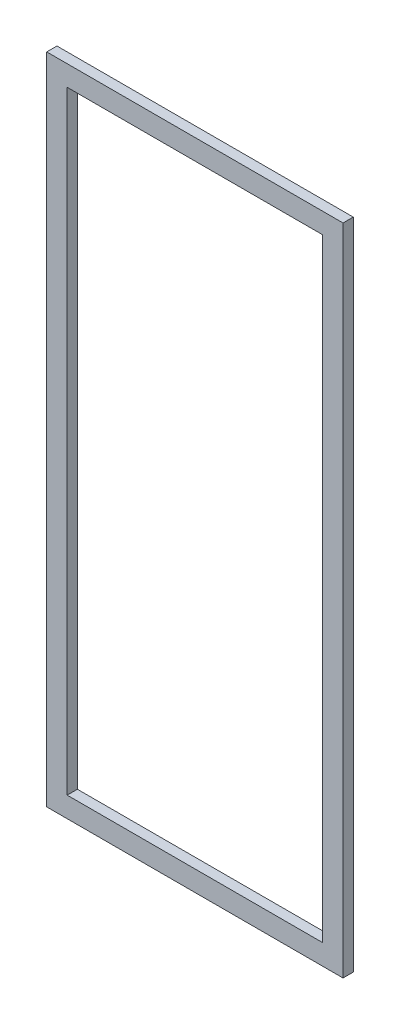
SolidWorks part; units mm, degrees
ref_plane "FP" through (0, 0, 0) normal (0, 0, 1) x (1, 0, 0)
ref_plane "TP" through (0, 0, 0) normal (0, 1, 0) x (1, 0, 0)
ref_plane "RP" through (0, 0, 0) normal (1, 0, 0) x (0, 0, -1)
sketch "Sketch2" plane through (0, 0, 0) normal (0, 0, 1) x (1, 0, 0)
  line L6 (-14.5, -32) -> (14.5, -32)
  line L7 (-14.5, -32) -> (-14.5, 32)
  line L8 (-14.5, 32) -> (14.5, 32)
  line L9 (14.5, -32) -> (14.5, 32)
  dimension "D1" = 64
  dimension "D2" = 32
  dimension "D3" = 29
  dimension "D4" = 14.5
extrude "Boss-Extrude1" add sketch "Sketch2" against normal blind 1
sketch "Sketch3" plane through (0, 0, 0) normal (0, 0, 1) x (1, 0, 0)
  line L1 (-12.5, -30) -> (12.5, -30)
  line L2 (-12.5, -30) -> (-12.5, 30)
  line L3 (-12.5, 30) -> (12.5, 30)
  line L4 (12.5, -30) -> (12.5, 30)
  line L5 (-12.5, -30) -> (12.5, 30) construction
  line L6 (-12.5, 30) -> (12.5, -30) construction
  point P0 (0, 0)
  dimension "D1" = 60
  dimension "D2" = 25
extrude "Cut-Extrude4" cut sketch "Sketch3" against normal blind 1 contours L1 L4 L3 L2
